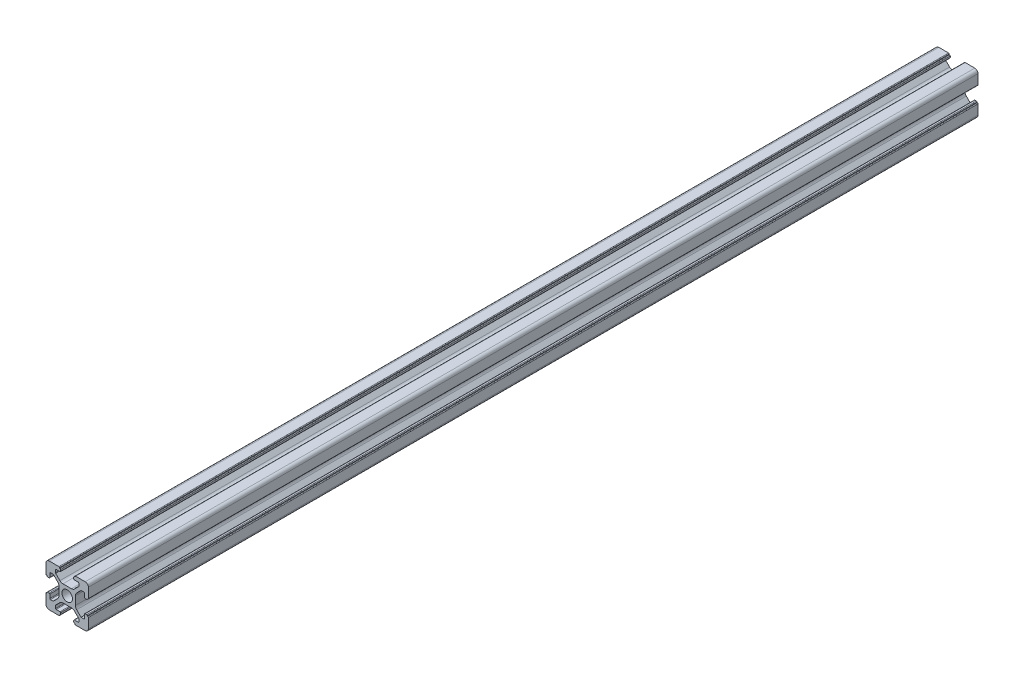
SolidWorks part; units mm, degrees
material "6063-T6，棒材(SS)"
ref_plane "前视基准面" through (0, 0, 0) normal (0, 0, 1) x (1, 0, 0)
ref_plane "上视基准面" through (0, 0, 0) normal (0, 1, 0) x (1, 0, 0)
ref_plane "右视基准面" through (0, 0, 0) normal (1, 0, 0) x (0, 0, -1)
sketch "中心线" plane through (0, 0, 0) normal (0, 0, 1) x (1, 0, 0)
  line L0 (7912.3831, 177.422) -> (7917.3831, 177.422) construction
  line L1 (7914.8831, 174.922) -> (7914.8831, 179.922) construction
sketch "截面" plane through (0, 0, 0) normal (0, 0, 1) x (1, 0, 0)
  line L0 (3961.9273, 92.1361) -> (3963.9144, 94.1231)
  line L1 (3964.1265, 94.211) -> (3965.3416, 94.211)
  line L2 (3965.6416, 93.911) -> (3965.6416, 92.111)
  line L3 (3965.9416, 91.811) -> (3966.6416, 91.811)
  line L4 (3966.9416, 92.111) -> (3966.9416, 92.311)
  line L5 (3966.9416, 92.311) -> (3967.1416, 92.311)
  line L6 (3967.4416, 92.611) -> (3967.4416, 97.211)
  line L7 (3965.9416, 98.711) -> (3961.3416, 98.711)
  line L8 (3961.0416, 98.411) -> (3961.0416, 98.211)
  line L9 (3961.0416, 98.211) -> (3960.8416, 98.211)
  line L10 (3960.5416, 97.911) -> (3960.5416, 97.211)
  line L11 (3960.8416, 96.911) -> (3962.6416, 96.911)
  line L12 (3962.9416, 96.611) -> (3962.9416, 95.3959)
  line L13 (3962.8537, 95.1838) -> (3960.8667, 93.1968)
  line L14 (3959.4525, 92.611) -> (3955.4306, 92.611)
  line L15 (3954.0164, 93.1968) -> (3952.0294, 95.1838)
  line L16 (3951.9416, 95.3959) -> (3951.9416, 96.611)
  line L17 (3952.2416, 96.911) -> (3954.0416, 96.911)
  line L18 (3954.3416, 97.211) -> (3954.3416, 97.911)
  line L19 (3954.0416, 98.211) -> (3953.8416, 98.211)
  line L20 (3953.8416, 98.211) -> (3953.8416, 98.411)
  line L21 (3953.5416, 98.711) -> (3948.9416, 98.711)
  line L22 (3947.4416, 97.211) -> (3947.4416, 92.611)
  line L23 (3947.7416, 92.311) -> (3947.9416, 92.311)
  line L24 (3947.9416, 92.311) -> (3947.9416, 92.111)
  line L25 (3948.2416, 91.811) -> (3948.9416, 91.811)
  line L26 (3949.2416, 92.111) -> (3949.2416, 93.911)
  line L27 (3949.5416, 94.211) -> (3950.7566, 94.211)
  line L28 (3950.9688, 94.1231) -> (3952.9558, 92.1361)
  line L29 (3953.5416, 90.7219) -> (3953.5416, 86.7001)
  line L30 (3952.9558, 85.2859) -> (3950.9688, 83.2989)
  line L31 (3950.7566, 83.211) -> (3949.5416, 83.211)
  line L32 (3949.2416, 83.511) -> (3949.2416, 85.311)
  line L33 (3948.9416, 85.611) -> (3948.2416, 85.611)
  line L34 (3947.9416, 85.311) -> (3947.9416, 85.111)
  line L35 (3947.9416, 85.111) -> (3947.7416, 85.111)
  line L36 (3947.4416, 84.811) -> (3947.4416, 80.211)
  line L37 (3948.9416, 78.711) -> (3953.5416, 78.711)
  line L38 (3954.3416, 79.511) -> (3954.3416, 80.211)
  line L39 (3954.0416, 80.511) -> (3952.2416, 80.511)
  line L40 (3951.9416, 80.811) -> (3951.9416, 82.0261)
  line L41 (3952.0294, 82.2382) -> (3954.0164, 84.2252)
  line L42 (3955.4306, 84.811) -> (3959.4525, 84.811)
  line L43 (3960.8667, 84.2252) -> (3962.8537, 82.2382)
  line L44 (3962.9416, 82.0261) -> (3962.9416, 80.811)
  line L45 (3962.6416, 80.511) -> (3960.8416, 80.511)
  line L46 (3960.5416, 80.211) -> (3960.5416, 79.511)
  line L47 (3961.3416, 78.711) -> (3965.9416, 78.711)
  line L48 (3967.4416, 80.211) -> (3967.4416, 84.811)
  line L49 (3967.1416, 85.111) -> (3966.9416, 85.111)
  line L50 (3966.9416, 85.111) -> (3966.9416, 85.311)
  line L51 (3966.6416, 85.611) -> (3965.9416, 85.611)
  line L52 (3965.6416, 85.311) -> (3965.6416, 83.511)
  line L53 (3965.3416, 83.211) -> (3964.0022, 83.211)
  line L54 (3964.0022, 83.211) -> (3961.9273, 85.2859)
  line L55 (3961.3416, 86.7001) -> (3961.3416, 90.7219)
  circle A0 centre (3957.4416, 88.711) radius 2.5
  arc A1 (3964.1265, 94.211) -> (3963.9144, 94.1231) centre (3964.1265, 93.911) ccw
  arc A2 (3965.6416, 93.911) -> (3965.3416, 94.211) centre (3965.3416, 93.911) ccw
  arc A3 (3965.6416, 92.111) -> (3965.9416, 91.811) centre (3965.9416, 92.111) ccw
  arc A4 (3966.6416, 91.811) -> (3966.9416, 92.111) centre (3966.6416, 92.111) ccw
  arc A5 (3967.1416, 92.311) -> (3967.4416, 92.611) centre (3967.1416, 92.611) ccw
  arc A6 (3967.4416, 97.211) -> (3965.9416, 98.711) centre (3965.9416, 97.211) ccw
  arc A7 (3961.3416, 98.711) -> (3961.0416, 98.411) centre (3961.3416, 98.411) ccw
  arc A8 (3960.8416, 98.211) -> (3960.5416, 97.911) centre (3960.8416, 97.911) ccw
  arc A9 (3960.5416, 97.211) -> (3960.8416, 96.911) centre (3960.8416, 97.211) ccw
  arc A10 (3962.9416, 96.611) -> (3962.6416, 96.911) centre (3962.6416, 96.611) ccw
  arc A11 (3962.8537, 95.1838) -> (3962.9416, 95.3959) centre (3962.6416, 95.3959) ccw
  arc A12 (3959.4525, 92.611) -> (3960.8667, 93.1968) centre (3959.4525, 94.611) ccw
  arc A13 (3954.0164, 93.1968) -> (3955.4306, 92.611) centre (3955.4306, 94.611) ccw
  arc A14 (3951.9416, 95.3959) -> (3952.0294, 95.1838) centre (3952.2416, 95.3959) ccw
  arc A15 (3952.2416, 96.911) -> (3951.9416, 96.611) centre (3952.2416, 96.611) ccw
  arc A16 (3954.0416, 96.911) -> (3954.3416, 97.211) centre (3954.0416, 97.211) ccw
  arc A17 (3954.3416, 97.911) -> (3954.0416, 98.211) centre (3954.0416, 97.911) ccw
  arc A18 (3953.8416, 98.411) -> (3953.5416, 98.711) centre (3953.5416, 98.411) ccw
  arc A19 (3948.9416, 98.711) -> (3947.4416, 97.211) centre (3948.9416, 97.211) ccw
  arc A20 (3947.4416, 92.611) -> (3947.7416, 92.311) centre (3947.7416, 92.611) ccw
  arc A21 (3947.9416, 92.111) -> (3948.2416, 91.811) centre (3948.2416, 92.111) ccw
  arc A22 (3948.9416, 91.811) -> (3949.2416, 92.111) centre (3948.9416, 92.111) ccw
  arc A23 (3949.5416, 94.211) -> (3949.2416, 93.911) centre (3949.5416, 93.911) ccw
  arc A24 (3950.9688, 94.1231) -> (3950.7566, 94.211) centre (3950.7566, 93.911) ccw
  arc A25 (3953.5416, 90.7219) -> (3952.9558, 92.1361) centre (3951.5416, 90.7219) ccw
  arc A26 (3952.9558, 85.2859) -> (3953.5416, 86.7001) centre (3951.5416, 86.7001) ccw
  arc A27 (3950.7566, 83.211) -> (3950.9688, 83.2989) centre (3950.7566, 83.511) ccw
  arc A28 (3949.2416, 83.511) -> (3949.5416, 83.211) centre (3949.5416, 83.511) ccw
  arc A29 (3949.2416, 85.311) -> (3948.9416, 85.611) centre (3948.9416, 85.311) ccw
  arc A30 (3948.2416, 85.611) -> (3947.9416, 85.311) centre (3948.2416, 85.311) ccw
  arc A31 (3947.7416, 85.111) -> (3947.4416, 84.811) centre (3947.7416, 84.811) ccw
  arc A32 (3947.4416, 80.211) -> (3948.9416, 78.711) centre (3948.9416, 80.211) ccw
  arc A33 (3953.5416, 78.711) -> (3953.8416, 79.011) centre (3953.5416, 79.011) ccw
  arc A34 (3954.0416, 79.211) -> (3953.8416, 79.011) centre (3954.0416, 79.011) ccw
  arc A35 (3954.0416, 79.211) -> (3954.3416, 79.511) centre (3954.0416, 79.511) ccw
  arc A36 (3954.3416, 80.211) -> (3954.0416, 80.511) centre (3954.0416, 80.211) ccw
  arc A37 (3951.9416, 80.811) -> (3952.2416, 80.511) centre (3952.2416, 80.811) ccw
  arc A38 (3952.0294, 82.2382) -> (3951.9416, 82.0261) centre (3952.2416, 82.0261) ccw
  arc A39 (3955.4306, 84.811) -> (3954.0164, 84.2252) centre (3955.4306, 82.811) ccw
  arc A40 (3960.8667, 84.2252) -> (3959.4525, 84.811) centre (3959.4525, 82.811) ccw
  arc A41 (3962.9416, 82.0261) -> (3962.8537, 82.2382) centre (3962.6416, 82.0261) ccw
  arc A42 (3962.6416, 80.511) -> (3962.9416, 80.811) centre (3962.6416, 80.811) ccw
  arc A43 (3960.8416, 80.511) -> (3960.5416, 80.211) centre (3960.8416, 80.211) ccw
  arc A44 (3960.5416, 79.511) -> (3960.8416, 79.211) centre (3960.8416, 79.511) ccw
  arc A45 (3961.0416, 79.011) -> (3960.8416, 79.211) centre (3960.8416, 79.011) ccw
  arc A46 (3961.0416, 79.011) -> (3961.3416, 78.711) centre (3961.3416, 79.011) ccw
  arc A47 (3965.9416, 78.711) -> (3967.4416, 80.211) centre (3965.9416, 80.211) ccw
  arc A48 (3967.4416, 84.811) -> (3967.1416, 85.111) centre (3967.1416, 84.811) ccw
  arc A49 (3966.9416, 85.311) -> (3966.6416, 85.611) centre (3966.6416, 85.311) ccw
  arc A50 (3965.9416, 85.611) -> (3965.6416, 85.311) centre (3965.9416, 85.311) ccw
  arc A51 (3965.3416, 83.211) -> (3965.6416, 83.511) centre (3965.3416, 83.511) ccw
  arc A52 (3961.3416, 86.7001) -> (3961.9273, 85.2859) centre (3963.3416, 86.7001) ccw
  arc A53 (3961.9273, 92.1361) -> (3961.3416, 90.7219) centre (3963.3416, 90.7219) ccw
  dimension "D1" = 20
extrude "凸台-拉伸1" add sketch "截面" along normal blind 420
